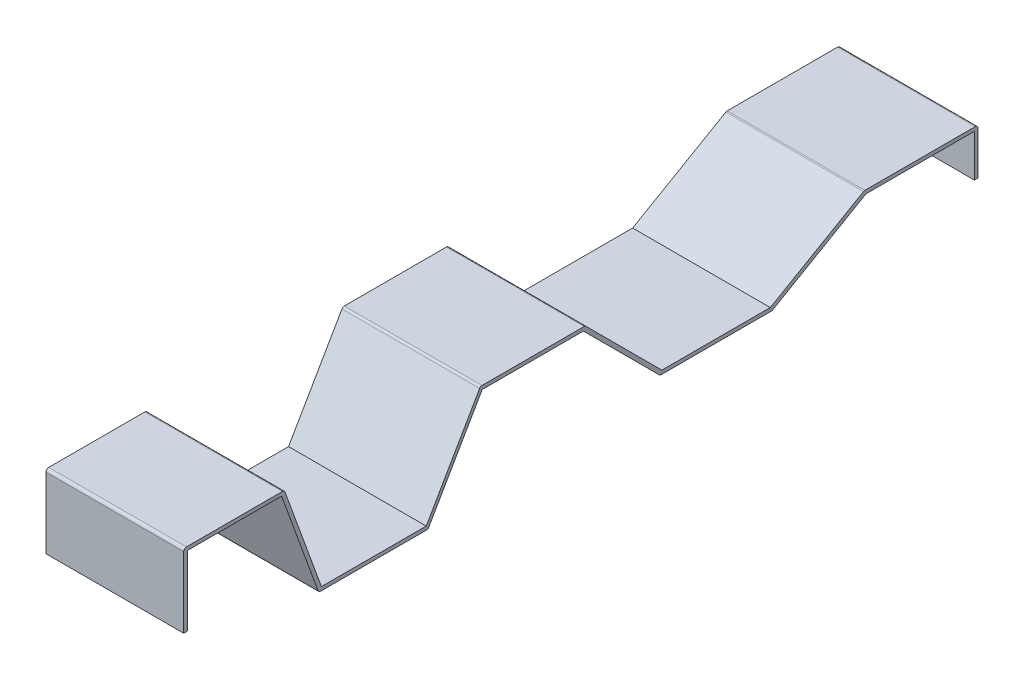
SolidWorks part; units mm, degrees
ref_plane "Front Plane" through (0, 0, 0) normal (0, 0, 1) x (1, 0, 0)
ref_plane "Top Plane" through (0, 0, 0) normal (0, 1, 0) x (1, 0, 0)
ref_plane "Right Plane" through (0, 0, 0) normal (1, 0, 0) x (0, 0, -1)
sketch "Sketch1" plane through (0, 0, 0) normal (1, 0, 0) x (0, 0, -1)
  line L0 (410.976, -727.738) -> (410.976, -702.338)
  line L1 (410.976, -702.338) -> (347.984, -702.338)
  line L2 (347.984, -702.338) -> (296.0225, -732.338)
  line L3 (296.0225, -732.338) -> (236.0225, -732.338)
  line L4 (236.0225, -732.338) -> (193.596, -689.9116)
  line L5 (193.596, -689.9116) -> (135.596, -689.9116)
  line L6 (135.596, -689.9116) -> (105.596, -741.8731)
  line L7 (105.596, -741.8731) -> (47.596, -741.8731)
  line L8 (47.596, -741.8731) -> (27.0748, -685.4916)
  line L9 (27.0748, -685.4916) -> (-28.6352, -685.4916)
  line L10 (-28.6352, -685.4916) -> (-28.6352, -726.1316)
  line L11 (410.976, -727.738) -> (408.976, -727.738)
  line L12 (408.976, -727.738) -> (408.976, -704.338)
  line L13 (408.976, -704.338) -> (348.976, -704.338)
  line L14 (348.976, -704.338) -> (297.0145, -734.338)
  line L15 (297.0145, -734.338) -> (235.0145, -734.338)
  line L16 (235.0145, -734.338) -> (192.588, -691.9116)
  line L17 (192.588, -691.9116) -> (136.588, -691.9116)
  line L18 (136.588, -691.9116) -> (106.588, -743.8731)
  line L19 (106.588, -743.8731) -> (46.088, -743.8731)
  line L20 (46.088, -743.8731) -> (25.5668, -687.4916)
  line L21 (25.5668, -687.4916) -> (-26.6352, -687.4916)
  line L22 (-26.6352, -687.4916) -> (-26.6352, -726.1316)
  line L23 (-26.6352, -726.1316) -> (-28.6352, -726.1316)
  dimension "D1" = 62.992
  dimension "D2" = 60
  dimension "D3" = 60
  dimension "D4" = 60
  dimension "D5" = 58
  dimension "D6" = 120
  dimension "D7" = 60
  dimension "D8" = 150
  dimension "D9" = 135
  dimension "D10" = 58
  dimension "D11" = 25.4
  dimension "D12" = 110
  dimension "D13" = 60
  dimension "D14" = 55.71
  dimension "D15" = 40.64
  dimension "D16" = 2
  dimension "D17" = 2
  dimension "D18" = 2
  dimension "D19" = 150
  dimension "D20" = 135
  dimension "D21" = 120
  dimension "D22" = 110
  dimension "D23" = 2
  dimension "D24" = 60
  dimension "D25" = 2
  dimension "D26" = 62
  dimension "D27" = 56
  dimension "D28" = 60
  dimension "D29" = 2
  dimension "D30" = 60.5
extrude "Boss-Extrude1" add sketch "Sketch1" along normal blind 76.2
fillet "Fillet1" radius 1.5 6 edges at (38.1, -702.338, -410.976) (38.1, -702.338, -347.984) (38.1, -689.9116, -193.596) (38.1, -689.9116, -135.596) (38.1, -685.4916, -27.0748) (38.1, -685.4916, 28.6352)
fillet "Fillet2" radius 1.5 4 edges at (38.1, -743.8731, -46.088) (38.1, -743.8731, -106.588) (38.1, -734.338, -235.0145) (38.1, -734.338, -297.0145)
fillet "Fillet3" radius 0.5 6 edges at (38.1, -704.338, -408.976) (38.1, -704.338, -348.976) (38.1, -691.9116, -192.588) (38.1, -691.9116, -136.588) (38.1, -687.4916, -25.5668) (38.1, -687.4916, 26.6352)
